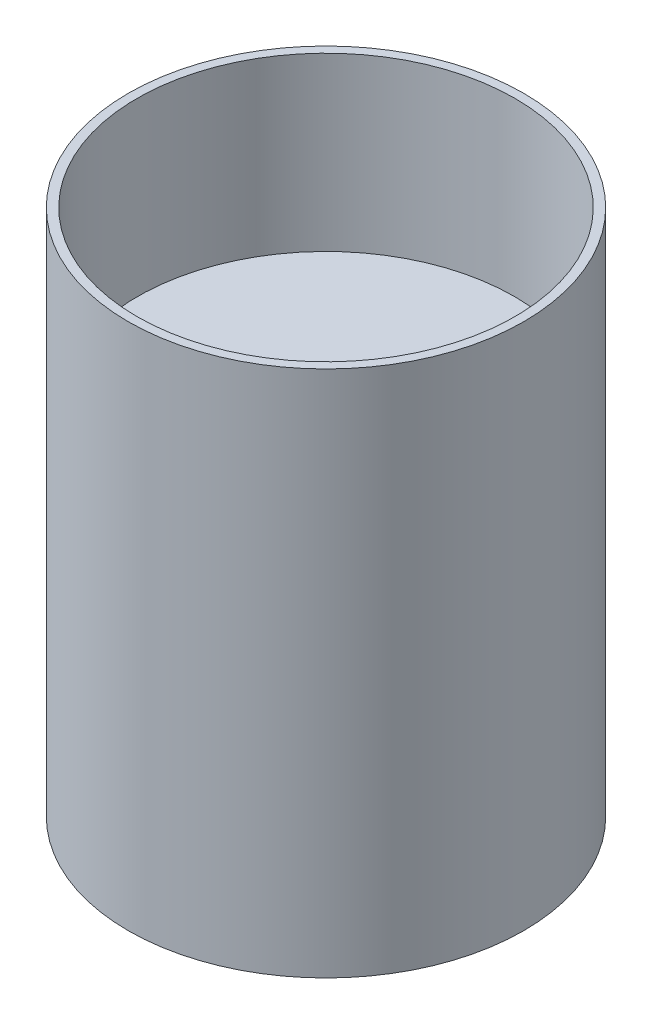
SolidWorks part; units mm, degrees
ref_plane "Front Plane" through (0, 0, 0) normal (0, 0, 1) x (1, 0, 0)
ref_plane "Top Plane" through (0, 0, 0) normal (0, 1, 0) x (1, 0, 0)
ref_plane "Right Plane" through (0, 0, 0) normal (1, 0, 0) x (0, 0, -1)
other "Configuration Table"
sketch "Sketch1" plane through (0, 0, 0) normal (0, 1, 0) x (1, 0, 0)
  circle A0 centre (0, 0) radius 45
  dimension "D1" = 90
extrude "Jar_Body" add sketch "Sketch1" along normal blind 120
sketch "Sketch2" plane through (0, 0, 0) normal (0, 1, 0) x (1, 0, 0)
  circle A0 centre (0, 0) radius 43
  dimension "D1" = 86
extrude "Jar_Cavity" cut sketch "Sketch2" along normal blind 120 from offset 3
sketch "Sketch3" plane through (0, 0, 0) normal (0, 1, 0) x (1, 0, 0)
  circle A0 centre (0, 0) radius 42.9
extrude "Water_Visual" add sketch "Sketch3" along normal blind 78 from offset 3 separate body
equation "\"jar_D\"= 90.0   'ASSUMPTION: Sensing jar rim outer diameter (PDF fallback)"
equation "\"jar_H\"= 120.0   'ASSUMPTION: Sensing jar height (PDF fallback)"
equation "\"jar_wall\"= 2.0   'ASSUMPTION: Jar wall thickness (designer choice)"
equation "\"jar_floor\"= 3.0   'ASSUMPTION: Jar floor thickness (designer choice)"
equation "\"D1@Sketch1\" = \"jar_D\""
equation "\"D1@Jar_Body\" = \"jar_H\""
equation "\"D1@Sketch2\" = \"jar_D\" - 2 * \"jar_wall\""
